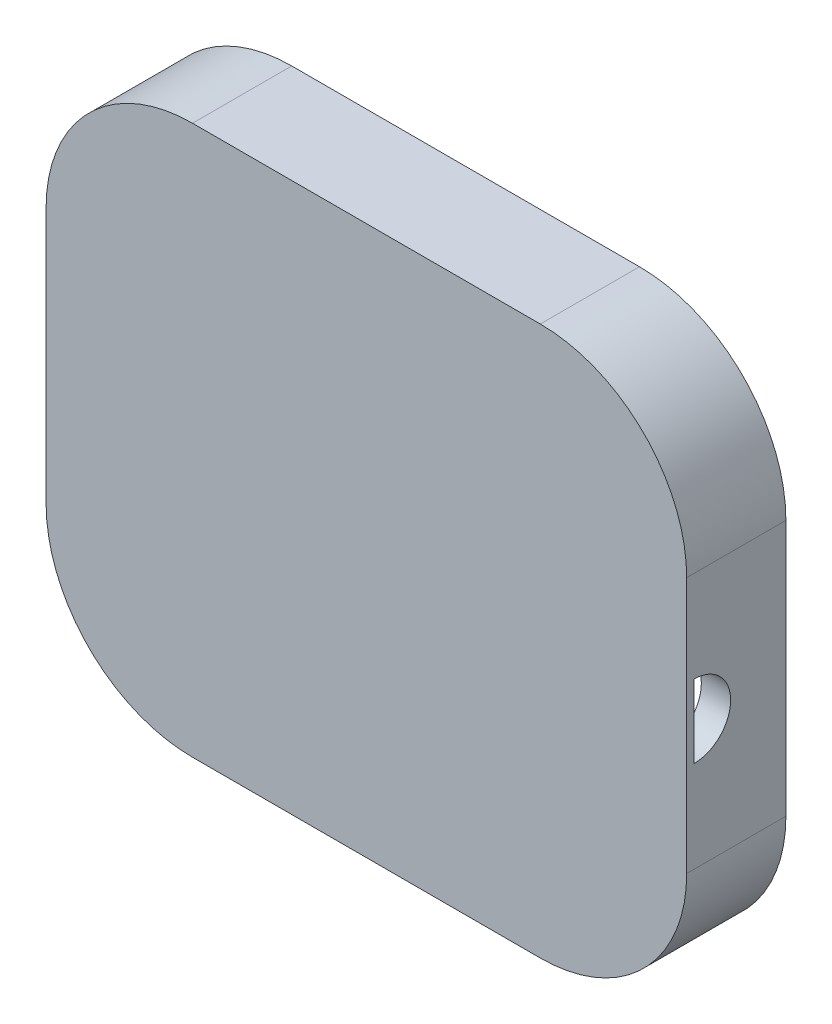
SolidWorks part; units mm, degrees
ref_plane "Plan de face" through (0, 0, 0) normal (0, 0, 1) x (1, 0, 0)
ref_plane "Plan de dessus" through (0, 0, 0) normal (0, 1, 0) x (1, 0, 0)
ref_plane "Plan de droite" through (0, 0, 0) normal (1, 0, 0) x (0, 0, -1)
sketch "Esquisse1" plane through (0, 0, 0) normal (0, 0, 1) x (1, 0, 0)
  line L0 (-75, 75) -> (75, -75) construction
  line L1 (-75, 75) -> (75, 75)
  line L2 (-75, 75) -> (-75, -75)
  line L3 (-75, -75) -> (75, -75)
  line L4 (75, 75) -> (75, -75)
  point P4 (0, 0)
  dimension "D1" = 150
  dimension "D2" = 150
extrude "Boss.-Extru.1" add sketch "Esquisse1" along normal blind 2
fillet "Congé1" radius 40 4 edges at (-75, -75, 1) (75, -75, 1) (-75, 75, 1) (75, 75, 1)
sketch "Esquisse9" plane through (0, 0, 2) normal (0, 0, 1) x (1, 0, 0)
  line L1 (35, 75) -> (100, 75)
  line L2 (100, -35) -> (100, 35)
  line L3 (100, -75) -> (100, 75)
  line L4 (100, -75) -> (35, -75)
  line L7 (75, -35) -> (75, 35)
  line L8 (75, -35) -> (75, 35)
  arc A4 (35, -75) -> (75, -35) centre (35, -35) ccw
  arc A5 (75, 35) -> (35, 75) centre (35, 35) ccw
  arc A6 (35, -75) -> (75, -35) centre (35, -35) ccw
  arc A7 (75, 35) -> (35, 75) centre (35, 35) ccw
  dimension "D2" = 0
  dimension "D1" = 25
extrude "Boss.-Extru.4" add sketch "Esquisse9" against normal blind 2
fillet "Congé2" radius 40 2 edges at (100, 75, 1) (100, -75, 1)
sketch "Esquisse5" plane through (0, 0, 0) normal (0, 0, -1) x (-1, 0, 0)
  line L0 (35, -75) -> (-60, -75) construction
  line L1 (75, 35) -> (75, -35) construction
  line L2 (-100, -35) -> (-100, 35) construction
  line L3 (-60, 75) -> (35, 75) construction
  line L4 (-100, 35) -> (-100, -35)
  line L5 (-60, -75) -> (35, -75)
  line L6 (75, -35) -> (75, 35)
  line L7 (35, 75) -> (-60, 75)
  line L12 (35, 67) -> (-60, 67)
  line L13 (67, -35) -> (67, 35)
  line L14 (-60, -67) -> (35, -67)
  line L15 (-92, 35) -> (-92, -35)
  arc A0 (75, 35) -> (35, 75) centre (35, 35) ccw construction
  arc A1 (35, -75) -> (75, -35) centre (35, -35) ccw construction
  arc A2 (-100, -35) -> (-60, -75) centre (-60, -35) ccw construction
  arc A4 (-100, -35) -> (-60, -75) centre (-60, -35) ccw
  arc A5 (35, -75) -> (75, -35) centre (35, -35) ccw
  arc A6 (75, 35) -> (35, 75) centre (35, 35) ccw
  arc A7 (-60, 75) -> (-100, 35) centre (-60, 35) ccw
  arc A12 (-60, 67) -> (-92, 35) centre (-60, 35) ccw
  arc A13 (67, 35) -> (35, 67) centre (35, 35) ccw
  arc A14 (35, -67) -> (67, -35) centre (35, -35) ccw
  arc A15 (-92, -35) -> (-60, -67) centre (-60, -35) ccw
  arc A24 (-60, 75) -> (-100, 35) centre (-60, 35) ccw construction
  dimension "D3" = 40
  dimension "D4" = 40
  dimension "D1" = 40
  dimension "D5" = 40
  dimension "D6" = 8
  dimension "D10" = 0
  dimension "D11" = 8
  dimension "D12" = 8
  dimension "D13" = 8
  dimension "D2" = 8
  dimension "D7" = 8
  dimension "D8" = 8
  dimension "D9" = 8
extrude "Boss.-Extru.3" add sketch "Esquisse5" along normal blind 25.1
sketch "Esquisse8" plane through (0, 0, -25.1) normal (0, 0, -1) x (-1, 0, 0)
  line L0 (-96, 0) -> (0, 0) construction
  line L1 (-100, 35) -> (-100, -35) construction
  line L2 (-12.5, 67) -> (-12.5, 71) construction
  line L3 (35, 67) -> (-60, 67) construction
  line L4 (67, 0) -> (71, 0) construction
  line L5 (67, -35) -> (67, 35) construction
  line L6 (-12.5, -67) -> (-12.5, -71) construction
  line L7 (-60, -67) -> (35, -67) construction
  circle A0 centre (-96, 0) radius 1.45
  circle A4 centre (-12.5, 71) radius 1.45
  circle A5 centre (71, 0) radius 1.45
  circle A6 centre (-12.5, -71) radius 1.45
  dimension "D1" = 4
  dimension "D2" = 2.9
  dimension "D3" = 4
extrude "Enlèv. mat.-Extru.4" cut sketch "Esquisse8" against normal blind 8
sketch "Esquisse10" plane through (100, 0, 0) normal (1, 0, 0) x (0, 0, -1)
  line L3 (0, 10) -> (0, -10)
  arc A1 (0, -10) -> (0, 10) centre (0, 0) ccw
  dimension "D1" = 20
extrude "Enlèv. mat.-Extru.6" cut sketch "Esquisse10" against normal blind 42
